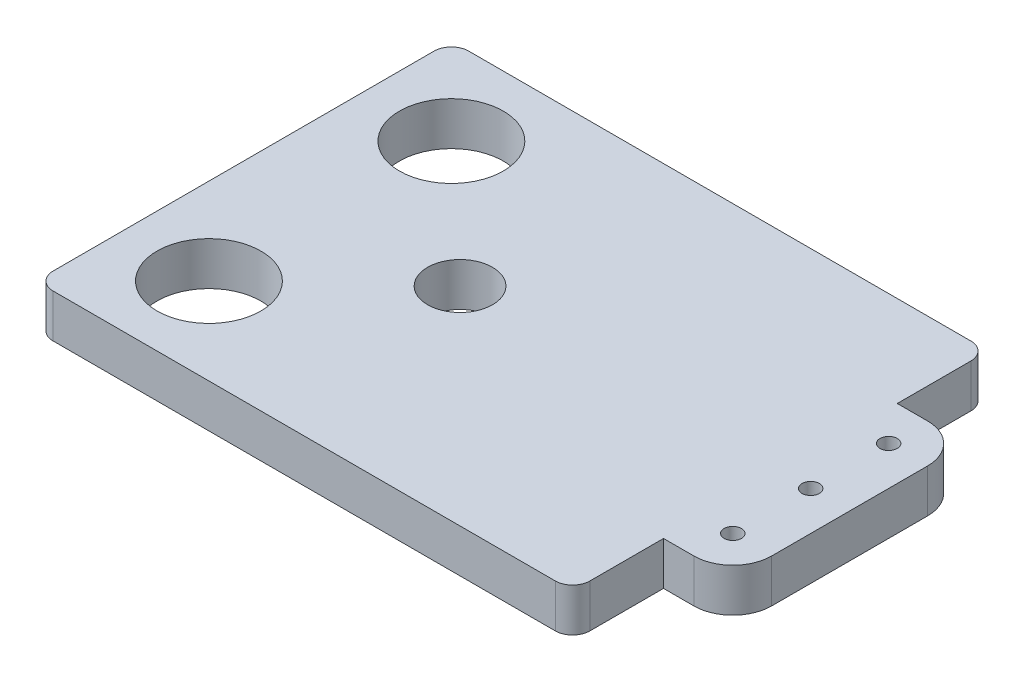
SolidWorks part; units mm, degrees
ref_plane "Front Plane" through (0, 0, 0) normal (0, 0, 1) x (1, 0, 0)
ref_plane "Top Plane" through (0, 0, 0) normal (0, 1, 0) x (1, 0, 0)
ref_plane "Right Plane" through (0, 0, 0) normal (1, 0, 0) x (0, 0, -1)
sketch "Sketch1" plane through (0, 0, 0) normal (0, 1, 0) x (1, 0, 0)
  line L0 (70, 33) -> (70, 15)
  line L1 (0, 0) -> (62, 0)
  line L2 (0, 0) -> (0, 48)
  line L3 (0, 48) -> (62, 48)
  line L5 (65.5, 37.5) -> (62, 37.5)
  line L7 (62, 48) -> (62, 37.5)
  line L17 (65.5, 10.5) -> (62, 10.5)
  line L18 (62, 10.5) -> (62, 0)
  circle A0 centre (10, 10) radius 6
  circle A1 centre (10, 38) radius 6
  circle A4 centre (25, 24) radius 3.75
  circle A8 centre (65.5, 15) radius 1
  circle A9 centre (65.5, 24) radius 1
  circle A10 centre (65.5, 33) radius 1
  arc A11 (70, 33) -> (65.5, 37.5) centre (65.5, 33) ccw
  arc A13 (65.5, 10.5) -> (70, 15) centre (65.5, 15) ccw
  point P15 (0, 24)
  dimension "D1" = 12
  dimension "D9" = 7.5
  dimension "D13" = 3.5
  dimension "D16" = 2
  dimension "D17" = 9
  dimension "D18" = 15
  dimension "D7" = 9
  dimension "D2" = 62
  dimension "D3" = 10
  dimension "D4" = 10
  dimension "D5" = 48
  dimension "D6" = 28
  dimension "D8" = 15
  dimension "D10" = 10.5
  dimension "D11" = 9
  dimension "D12" = 10.5
extrude "Boss-Extrude1" add sketch "Sketch1" along normal blind 5
fillet "Fillet1" radius 2 4 edges at (62, 2.5, -48) (62, 2.5, 0) (0, 2.5, -48) (0, 2.5, 0)
